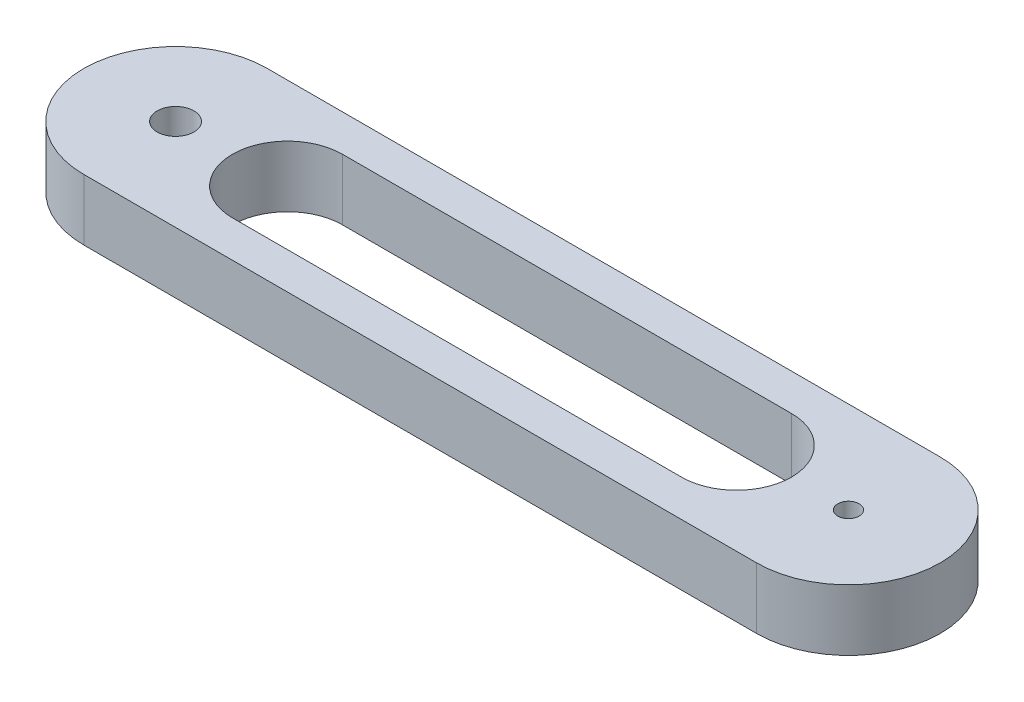
SolidWorks part; units mm, degrees
ref_plane "Front Plane" through (0, 0, 0) normal (0, 0, 1) x (1, 0, 0)
ref_plane "Top Plane" through (0, 0, 0) normal (0, 1, 0) x (1, 0, 0)
ref_plane "Right Plane" through (0, 0, 0) normal (1, 0, 0) x (0, 0, -1)
sketch "Sketch2" plane through (0, 0, 0) normal (0, 1, 0) x (1, 0, 0)
  line L0 (0, 0) -> (110, 0) construction
  line L1 (0, 15) -> (110, 15)
  line L2 (0, -15) -> (110, -15)
  arc A0 (0, 15) -> (0, -15) centre (0, 0) ccw
  arc A1 (110, -15) -> (110, 15) centre (110, 0) ccw
  circle A2 centre (0, 0) radius 1.45
  circle A3 centre (110, 0) radius 1.5
  point P3 (55, 0)
  dimension "D2" = 15
  dimension "D3" = 2.9
  dimension "D4" = 3
  dimension "D1" = 110
extrude "Boss-Extrude1" add sketch "Sketch2" along normal blind 10
sketch "Sketch3" plane through (0, 10, 0) normal (0, 1, 0) x (1, 0, 0)
  circle A1 centre (0, 0) radius 2.925
  dimension "D1" = 5.85
extrude "Cut-Extrude1" cut sketch "Sketch3" against normal blind 2
sketch "Sketch4" plane through (0, 10, 0) normal (0, 1, 0) x (1, 0, 0)
  line L0 (18.2957, 0) -> (91.7, 0) construction
  line L1 (18.2957, 9) -> (91.7, 9)
  line L2 (18.2957, -9) -> (91.7, -9)
  line L3 (110, 15) -> (0, 15) construction
  arc A0 (18.2957, 9) -> (18.2957, -9) centre (18.2957, 0) ccw
  arc A1 (91.7, -9) -> (91.7, 9) centre (91.7, 0) ccw
  circle A2 centre (110, 0) radius 1.5 construction
  point P3 (54.9979, 0)
  point P12 (100.7, 0)
  dimension "D1" = 6
  dimension "D2" = 9.3
extrude "Cut-Extrude2" cut sketch "Sketch4" against normal blind 10
sketch "Sketch5" plane through (0, 10, 0) normal (0, 1, 0) x (1, 0, 0)
  circle A0 centre (0, 0) radius 3
  dimension "D1" = 6
extrude "Cut-Extrude3" cut sketch "Sketch5" against normal blind 10
sketch "Sketch6" plane through (0, 10, 0) normal (0, 1, 0) x (1, 0, 0)
  circle A0 centre (110, 0) radius 1.75
  dimension "D1" = 3.5
extrude "Cut-Extrude4" cut sketch "Sketch6" against normal blind 10
